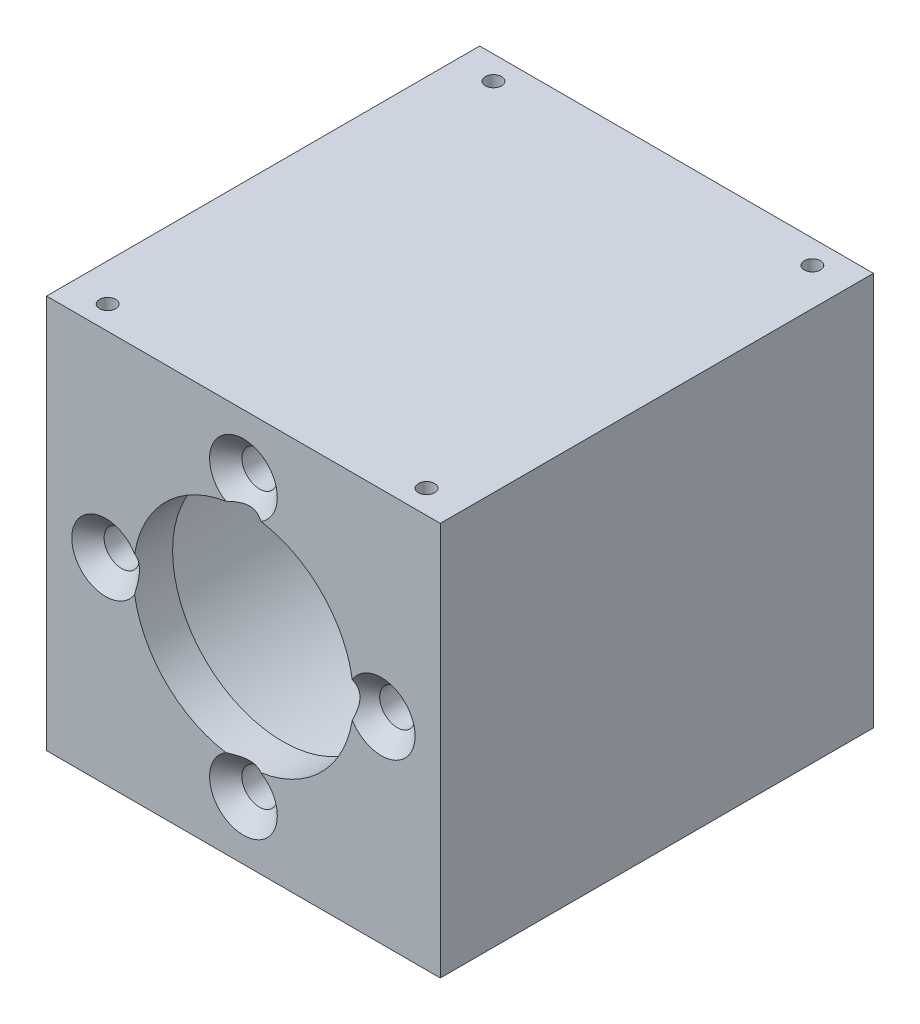
SolidWorks part; units mm, degrees
material "6061 合金"
ref_plane "前视基准面" through (0, 0, 0) normal (0, 0, 1) x (1, 0, 0)
ref_plane "上视基准面" through (0, 0, 0) normal (0, 1, 0) x (1, 0, 0)
ref_plane "右视基准面" through (0, 0, 0) normal (1, 0, 0) x (0, 0, -1)
sketch "草图1" plane through (0, 0, 0) normal (0, 0, 1) x (1, 0, 0)
  line L1 (-25, -25) -> (25, -25)
  line L2 (-25, -25) -> (-25, 25)
  line L3 (-25, 25) -> (25, 25)
  line L4 (25, -25) -> (25, 25)
  line L5 (-25, -25) -> (25, 25) construction
  line L6 (-25, 25) -> (25, -25) construction
  circle A0 centre (0, 0) radius 21 construction
  circle A1 centre (0, 0) radius 14
  point P0 (0, 0)
  dimension "D1" = 42
  dimension "D2" = 4
  dimension "D4" = 4
  dimension "D5" = 28
  dimension "D3" = 4
extrude "凸台-拉伸2" add sketch "草图1" along normal mid plane 55
sketch "草图11" plane through (0, -25, 0) normal (0, -1, 0) x (1, 0, 0)
  line L1 (-25, 27.5) -> (25, 27.5) construction
  line L2 (-35, -27.5) -> (35, -27.5)
  line L3 (-35, -27.5) -> (-35, 27.5)
  line L4 (-35, 27.5) -> (35, 27.5)
  line L5 (35, -27.5) -> (35, 27.5)
  line L7 (-35, -27.5) -> (35, 27.5) construction
  line L8 (-35, 27.5) -> (35, -27.5) construction
  line L9 (-25, -27.5) -> (25, -27.5) construction
  line L10 (25, 27.5) -> (25, -27.5) construction
  point P0 (0, 0)
  dimension "D1" = 10
extrude "凸台-拉伸3" [suppressed] add sketch "草图11" against normal blind 10
sketch "草图3" plane through (0, 0, -27.5) normal (0, 0, -1) x (-1, 0, 0)
  circle A0 centre (0, 0) radius 21
  dimension "D1" = 42
extrude "切除-拉伸2" cut sketch "草图3" against normal offset from surface (50 mm away) 5 up to face at (0, 0, 27.5)
hole_wizard "M2.5 螺纹孔1" positions "草图7" profile "草图9" tap size "M2.5" standard "GB"
sketch "草图7" plane through (-9.644, 25, 9.7146) normal (0, 1, 0) x (1, 0, 0)
  line L0 (9.644, 9.7146) -> (9.644, -42.6299) construction
  line L3 (-10.606, -14.7854) -> (29.894, -14.7854) construction
  line L4 (-10.606, -14.7854) -> (-10.606, 34.2146) construction
  line L5 (-10.606, 34.2146) -> (29.894, 34.2146) construction
  line L6 (29.894, -14.7854) -> (29.894, 34.2146) construction
  line L7 (-10.606, -14.7854) -> (29.894, 34.2146) construction
  line L8 (-10.606, 34.2146) -> (29.894, -14.7854) construction
  line L10 (34.644, 37.2146) -> (-15.356, 37.2146) construction
  point P7 (29.894, 34.2146)
  point P92 (-10.606, -14.7854)
  point P93 (-10.606, 34.2146)
  point P94 (29.894, -14.7854)
  dimension "D1" = 40.5
  dimension "D2" = 49
  dimension "D3" = 3
sketch "草图9" plane through (20.25, 25, -24.5) normal (1, 0, 0) x (0, 0, 1)
  line L0 (0, 0) -> (0, 7.8659)
  line L1 (0, 7.8659) -> (1.025, 7.25)
  line L2 (1.025, 7.25) -> (1.025, 0)
  line L5 (1.025, 0) -> (0, 0)
  line L10 (0, 7.8659) -> (-1.025, 7.25) construction
  line L11 (0, -6.35) -> (0, 107.95) construction
  dimension "螺纹孔钻头直径" = 2.05
  dimension "螺纹孔钻头深度" = 7.25
  dimension "导头角度" = 118
cosmetic thread "孔螺蚊线1" parameters "D1"=5, "D2"=2.5
cosmetic thread "孔螺蚊线4" parameters "D1"=5, "D2"=2.5
cosmetic thread "孔螺蚊线5" parameters "D1"=5, "D2"=2.5
cosmetic thread "孔螺蚊线6" parameters "D1"=5, "D2"=2.5
hole_wizard "打孔尺寸(%根据十字)槽沉头木螺钉的类型1" positions "草图5" profile "草图4" countersink size "M4" standard "GB" end condition up to next
sketch "草图5" plane through (0, 0, 27.5) normal (0, 0, 1) x (1, 0, 0)
  circle A0 centre (0, 0) radius 17.5 construction
  point P5 (0, 17.5)
  point P26 (17.5, 0)
  point P27 (0, -17.5)
  point P28 (-17.5, 0)
  dimension "D1" = 35
  dimension "D2" = 4
sketch "草图4" plane through (0, 17.5, 27.5) normal (1, 0, 0) x (0, -1, 0)
  line L0 (0, 0) -> (0, 5)
  line L1 (0, 5) -> (2.25, 5)
  line L2 (2.25, 5) -> (2.25, 2.05)
  line L3 (2.25, 2.05) -> (4.3, 0)
  line L5 (4.3, 0) -> (0, 0)
  line L6 (-2.25, 2.05) -> (-4.3, 0) construction
  line L11 (0, -6.35) -> (0, 107.95) construction
  dimension "通孔孔直径" = 4.5
  dimension "通孔孔深度" = 5
  dimension "近端锥形沉头孔直径" = 8.6
  dimension "近端锥形沉头孔角度" = 90
hole_wizard "M4 螺纹孔1" positions "草图13" profile "草图12" tap size "M4" standard "GB"
sketch "草图13" plane through (0.5, -25, 0) normal (0, 1, 0) x (0, 0, 1)
  line L1 (-23.5, 20.5) -> (23.5, 20.5)
  line L2 (-23.5, 20.5) -> (-23.5, -21.5)
  line L3 (-23.5, -21.5) -> (23.5, -21.5)
  line L4 (23.5, 20.5) -> (23.5, -21.5)
  line L5 (-23.5, 20.5) -> (23.5, -21.5) construction
  line L6 (-23.5, -21.5) -> (23.5, 20.5) construction
  line L7 (0, -0.5) -> (-23.5, -0.5) construction
  line L11 (0, 20.5) -> (0, -25.5) construction
  line L12 (27.5, -25.5) -> (-27.5, -25.5) construction
  line L15 (-27.5, -25.5) -> (-27.5, 24.5) construction
  point P2 (23.5, -21.5)
  point P5 (-23.5, 20.5)
  point P6 (-23.5, -21.5)
  point P7 (23.5, 20.5)
  dimension "D1" = 4
  dimension "D2" = 4
sketch "草图12" plane through (-21, -25, 23.5) normal (1, 0, 0) x (0, 0, -1)
  line L0 (0, 0) -> (0, 9.0914)
  line L1 (0, 9.0914) -> (1.65, 8.1)
  line L2 (1.65, 8.1) -> (1.65, 0)
  line L5 (1.65, 0) -> (0, 0)
  line L10 (0, 9.0914) -> (-1.65, 8.1) construction
  line L11 (0, -6.35) -> (0, 107.95) construction
  dimension "螺纹孔钻头直径" = 3.3
  dimension "螺纹孔钻头深度" = 8.1
  dimension "导头角度" = 118
cosmetic thread "孔螺蚊线11" parameters "D1"=6, "D2"=4
cosmetic thread "孔螺蚊线12" parameters "D1"=6, "D2"=4
cosmetic thread "孔螺蚊线13" parameters "D1"=6, "D2"=4
cosmetic thread "孔螺蚊线14" parameters "D1"=6, "D2"=4
